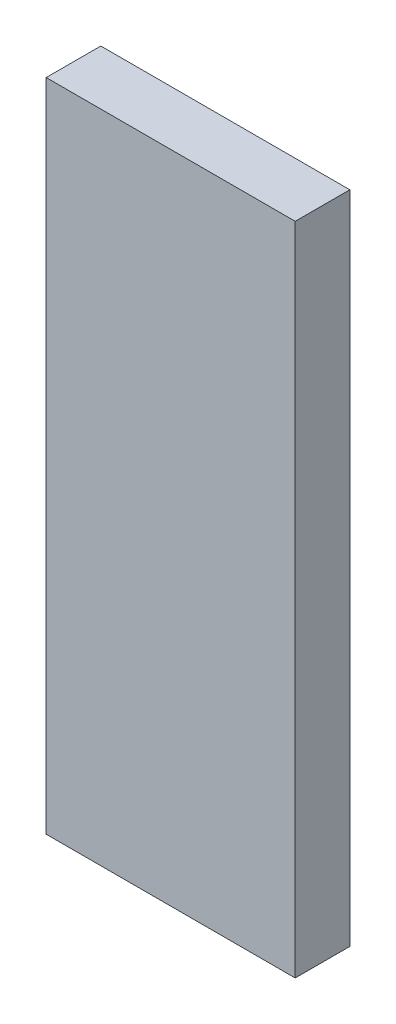
SolidWorks part; units mm, degrees
ref_plane "Front Plane" through (0, 0, 0) normal (0, 0, 1) x (1, 0, 0)
ref_plane "Top Plane" through (0, 0, 0) normal (0, 1, 0) x (1, 0, 0)
ref_plane "Right Plane" through (0, 0, 0) normal (1, 0, 0) x (0, 0, -1)
sketch "Sketch1" plane through (0, 0, 0) normal (0, 0, 1) x (1, 0, 0)
  line L1 (0, 0) -> (14.478, 0)
  line L2 (0, 0) -> (0, 38.1)
  line L3 (0, 38.1) -> (14.478, 38.1)
  line L4 (14.478, 0) -> (14.478, 38.1)
  dimension "D1" = 14.478
  dimension "D2" = 38.1
extrude "Boss-Extrude1" add sketch "Sketch1" along normal blind 3.175
